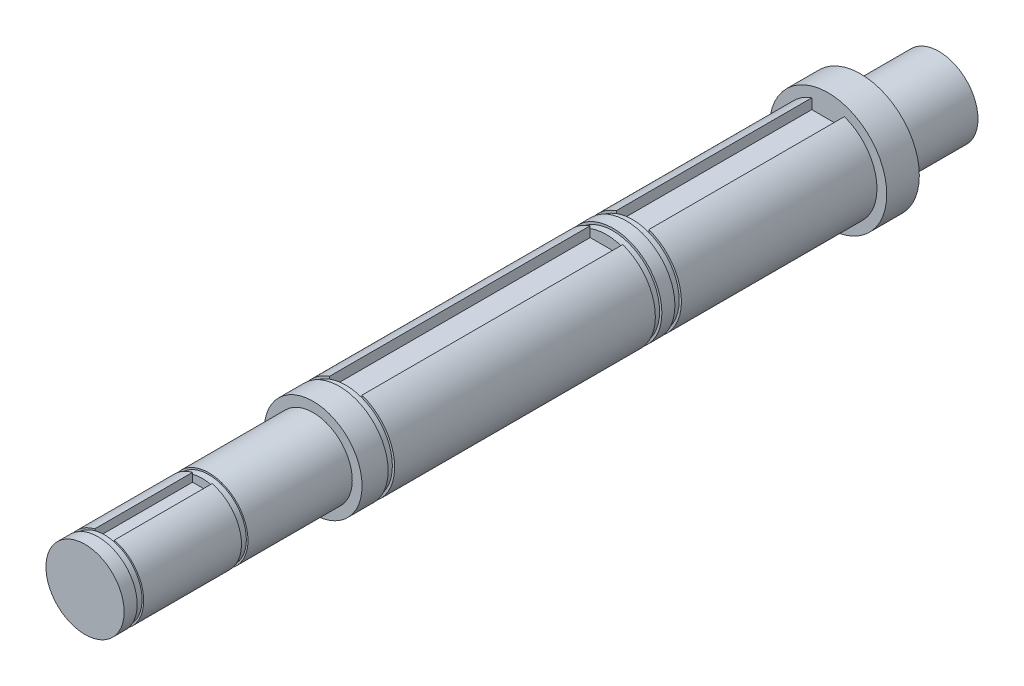
SolidWorks part; units mm, degrees
ref_plane "Front Plane" through (0, 0, 0) normal (0, 0, 1) x (1, 0, 0)
ref_plane "Top Plane" through (0, 0, 0) normal (0, 1, 0) x (1, 0, 0)
ref_plane "Right Plane" through (0, 0, 0) normal (1, 0, 0) x (0, 0, -1)
sketch "Sketch5" plane through (0, 0, 0) normal (1, 0, 0) x (0, 0, -1)
  line L0 (0, 0) -> (95.6046, 0) construction
  line L1 (0, 0) -> (0, 6)
  line L2 (0, 6) -> (12, 6)
  line L3 (12, 6) -> (12, 7.5)
  line L4 (12, 7.5) -> (91, 7.5)
  line L5 (91, 7.5) -> (91, 9)
  line L6 (91, 9) -> (96, 9)
  line L7 (96, 9) -> (96, 6)
  line L8 (96, 6) -> (108, 6)
  line L9 (108, 6) -> (108, 0)
  line L10 (108, 0) -> (0, 0)
  dimension "D1" = 84
  dimension "D2" = 12
  dimension "D3" = 12
  dimension "D4" = 5
  dimension "D5" = 12
  dimension "D6" = 12
  dimension "D7" = 9
  dimension "D8" = 15
revolve "Revolve1" add sketch "Sketch5" angle 360 about L0
sketch "Sketch7" plane through (0, 0, 0) normal (0, 0, 1) x (1, 0, 0)
  circle A0 centre (0, 0) radius 7.15
  circle A1 centre (0, 0) radius 10.15
  dimension "D1" = 14.3
  dimension "D2" = 3
extrude "Cut-Extrude2" cut sketch "Sketch7" against normal blind 1 from offset 16 offset against normal yes
sketch "Sketch10" plane through (0, 0, -17) normal (0, 0, 1) x (1, 0, 0)
  line L0 (2.5, 5.5) -> (-2.5, 5.5)
  line L2 (2.5, 5.5) -> (2.5, 8.5)
  line L4 (2.5, 8.5) -> (-2.5, 8.5)
  line L5 (-2.5, 5.5) -> (-2.5, 8.5)
  point P0 (0, 5.5)
  dimension "D1" = 5
  dimension "D2" = 5.5
  dimension "D3" = 3
extrude "Cut-Extrude3" cut sketch "Sketch10" against normal blind 40
sketch "Sketch11" plane through (0, 0, -57) normal (0, 0, 1) x (1, 0, 0)
  circle A0 centre (0, 0) radius 10.15
  circle A1 centre (0, 0) radius 7.15
  dimension "D1" = 3
  dimension "D2" = 14.3
extrude "Cut-Extrude4" cut sketch "Sketch11" against normal blind 1
sketch "Sketch13" plane through (0, 0, -57) normal (0, 0, 1) x (1, 0, 0)
  circle A0 centre (0, 0) radius 10.15
  circle A1 centre (0, 0) radius 7.15
  dimension "D1" = 3
  dimension "D2" = 14.3
extrude "Cut-Extrude5" cut sketch "Sketch13" against normal blind 1 from offset 3 offset against normal yes
sketch "Sketch14" plane through (0, 0, 0) normal (0, 0, 1) x (1, 0, 0)
  line L0 (2.5, 5.5) -> (-2.5, 5.5)
  line L2 (2.5, 5.5) -> (2.5, 8.5)
  line L4 (2.5, 8.5) -> (-2.5, 8.5)
  line L5 (-2.5, 5.5) -> (-2.5, 8.5)
  dimension "D1" = 5
  dimension "D3" = 3
extrude "Cut-Extrude6" cut sketch "Sketch14" against normal blind 30 from offset 61 offset against normal yes
sketch "Sketch15" plane through (0, 0, 0) normal (0, 0, 1) x (1, 0, 0)
  circle A0 centre (0, 0) radius 6
  dimension "D1" = 12
extrude "Boss-Extrude4" add sketch "Sketch15" along normal blind 20
sketch "Sketch16" plane through (0, 0, 20) normal (0, 0, 1) x (1, 0, 0)
  line L0 (-1.5, 6) -> (1.5, 6)
  line L1 (-1.5, 6) -> (-1.5, 4.5)
  line L2 (-1.5, 4.5) -> (1.5, 4.5)
  line L3 (1.5, 6) -> (1.5, 4.5)
  circle A0 centre (0, 0) radius 6 construction
  point P4 (0, 4.5)
  point P5 (0, 6)
  dimension "D1" = 1.5
  dimension "D2" = 3
extrude "Cut-Extrude7" cut sketch "Sketch16" against normal blind 15
sketch "Sketch17" plane through (0, 0, 20) normal (0, 0, 1) x (1, 0, 0)
  circle A0 centre (0, 0) radius 6
  dimension "D1" = 12
extrude "Boss-Extrude5" add sketch "Sketch17" along normal blind 3
sketch "Sketch18" plane through (0, 0, 20) normal (0, 0, -1) x (-1, 0, 0)
  circle A0 centre (0, 0) radius 5.75
  circle A1 centre (0, 0) radius 6.5
  dimension "D1" = 11.5
  dimension "D2" = 13
extrude "Cut-Extrude8" cut sketch "Sketch18" against normal blind 1
sketch "Sketch19" plane through (0, 0, 5) normal (0, 0, 1) x (1, 0, 0)
  circle A0 centre (0, 0) radius 6.5
  circle A1 centre (0, 0) radius 5.75
  dimension "D1" = 11.5
  dimension "D2" = 13
extrude "Cut-Extrude9" cut sketch "Sketch19" against normal blind 1
